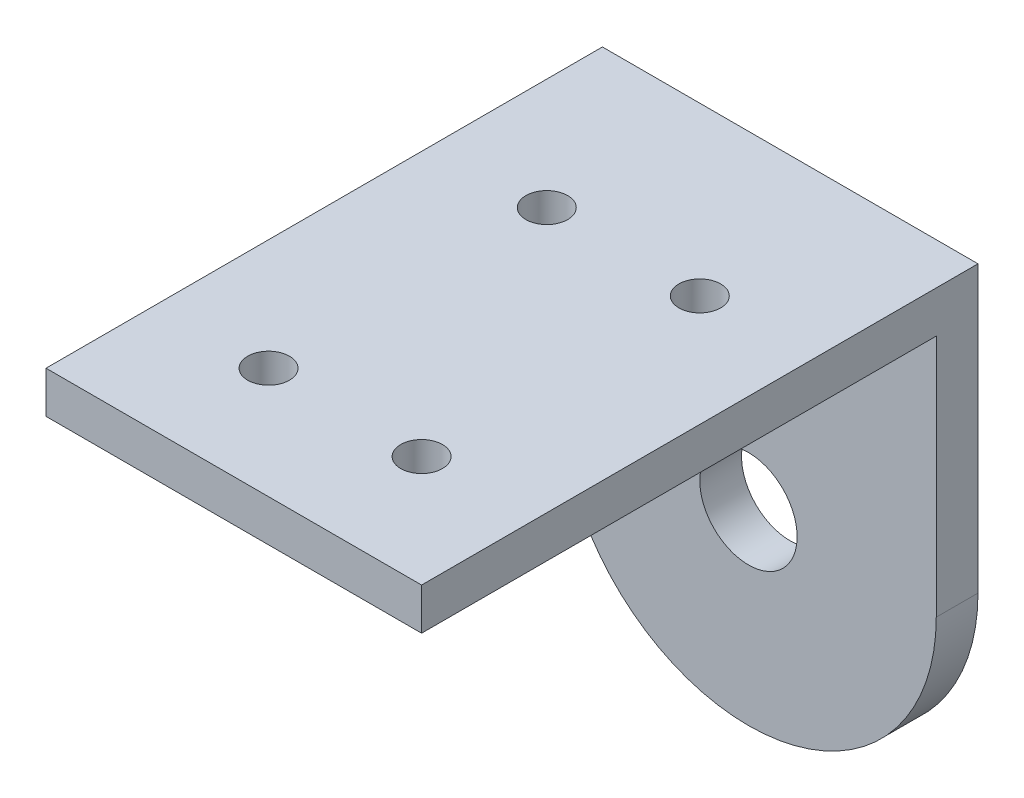
SolidWorks part; units mm, degrees
ref_plane "前视基准面" through (0, 0, 0) normal (0, 0, 1) x (1, 0, 0)
ref_plane "上视基准面" through (0, 0, 0) normal (0, 1, 0) x (1, 0, 0)
ref_plane "右视基准面" through (0, 0, 0) normal (1, 0, 0) x (0, 0, -1)
sketch "Model" plane through (0, 0, 0) normal (0, 0, 1) x (1, 0, 0)
  line L0 (2619.7667, 1592.8264) -> (2619.7667, 1613.3264)
  line L1 (2592.7667, 1592.8264) -> (2592.7667, 1613.3264)
  line L2 (2592.7667, 1613.3264) -> (2619.7667, 1613.3264)
  circle A0 centre (2606.2667, 1592.8264) radius 3.5
  arc A1 (2592.7667, 1592.8264) -> (2619.7667, 1592.8264) centre (2606.2667, 1592.8264) ccw
  dimension "D1" = 20.5
extrude "凸台-拉伸1" add sketch "Model" along normal blind 40
sketch "草图3" plane through (2619.7667, 0, 0) normal (1, 0, 0) x (0, 0, -1)
  line L0 (-40, 1592.8264) -> (-40, 1613.3264) construction
  line L1 (-40, 1610.3264) -> (-3, 1610.3264)
  line L2 (-40, 1610.3264) -> (-40, 1573.3264)
  line L3 (-40, 1573.3264) -> (-3, 1573.3264)
  line L4 (-3, 1610.3264) -> (-3, 1573.3264)
  line L5 (-40, 1613.3264) -> (0, 1613.3264) construction
  line L6 (0, 1592.8264) -> (0, 1613.3264) construction
  dimension "D1" = 3
  dimension "D2" = 3
  dimension "D3" = 40
extrude "切除-拉伸1" cut sketch "草图3" against normal blind 40
sketch "草图4" plane through (0, 1613.3264, 0) normal (0, 1, 0) x (1, 0, 0)
  line L6 (2619.7667, -40) -> (2619.7667, -32)
  circle A0 centre (2600.7667, -32) radius 1.5
  circle A1 centre (2611.7667, -32) radius 1.5
  circle A2 centre (2600.7667, -12) radius 1.5
  circle A3 centre (2611.7667, -12) radius 1.5
  dimension "D7" = 3
  dimension "D8" = 3
  dimension "D9" = 3
  dimension "D10" = 3
extrude "切除-拉伸2" cut sketch "草图4" against normal blind 40 contours A0 | A1 | A3 | A2
